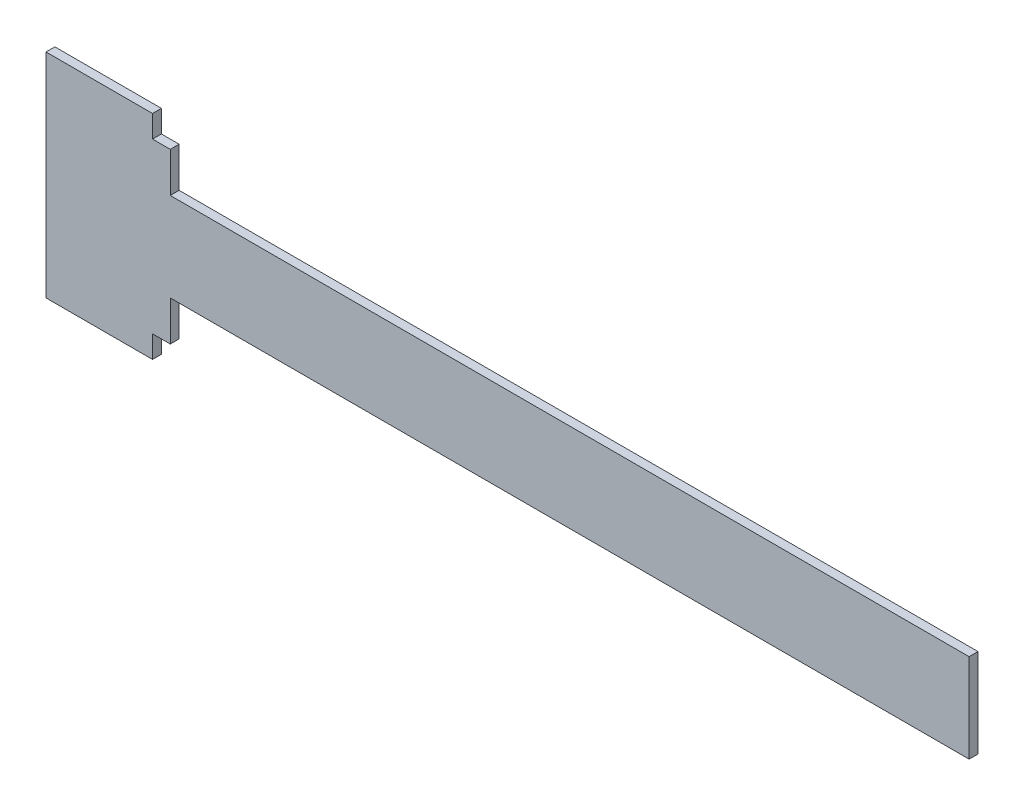
SolidWorks part; units mm, degrees
ref_plane "前视基准面" through (0, 0, 0) normal (0, 0, 1) x (1, 0, 0)
ref_plane "上视基准面" through (0, 0, 0) normal (0, 1, 0) x (1, 0, 0)
ref_plane "右视基准面" through (0, 0, 0) normal (1, 0, 0) x (0, 0, -1)
sketch "草图1" plane through (0, 0, 0) normal (0, 0, 1) x (1, 0, 0)
  line L0 (-68.9761, 1.5224) -> (-68.9761, -0.9776)
  line L1 (-68.9761, 20.5224) -> (-66.9761, 20.5224)
  line L3 (-68.9761, 1.5224) -> (-66.9761, 1.5224)
  line L4 (-66.9761, 20.5224) -> (-66.9761, 16.0224)
  line L7 (-80.9761, 23.0224) -> (-68.9761, 23.0224)
  line L8 (-66.9761, 16.0224) -> (23.0239, 16.0224)
  line L10 (-66.9761, 6.0224) -> (23.0239, 6.0224)
  line L11 (23.0239, 16.0224) -> (23.0239, 6.0224)
  line L14 (-80.9761, 23.0224) -> (-80.9761, -0.9776)
  line L15 (-80.9761, -0.9776) -> (-68.9761, -0.9776)
  line L16 (-68.9761, 23.0224) -> (-68.9761, 20.5224)
  line L19 (-66.9761, 6.0224) -> (-66.9761, 1.5224)
  point P0 (-67.9761, 11.0224)
  point P5 (-76.5616, 10.8147)
  point P6 (-21.9761, 11.0224)
  point P12 (-74.9761, 11.0224)
  dimension "D1" = 19
  dimension "D2" = 2
  dimension "D3" = 90
  dimension "D4" = 10
  dimension "D5" = 2.5
  dimension "D6" = 2.5
  dimension "D7" = 4.5
  dimension "D8" = 4.5
  dimension "D9" = 12
extrude "凸台-拉伸1" add sketch "草图1" along normal blind 1
